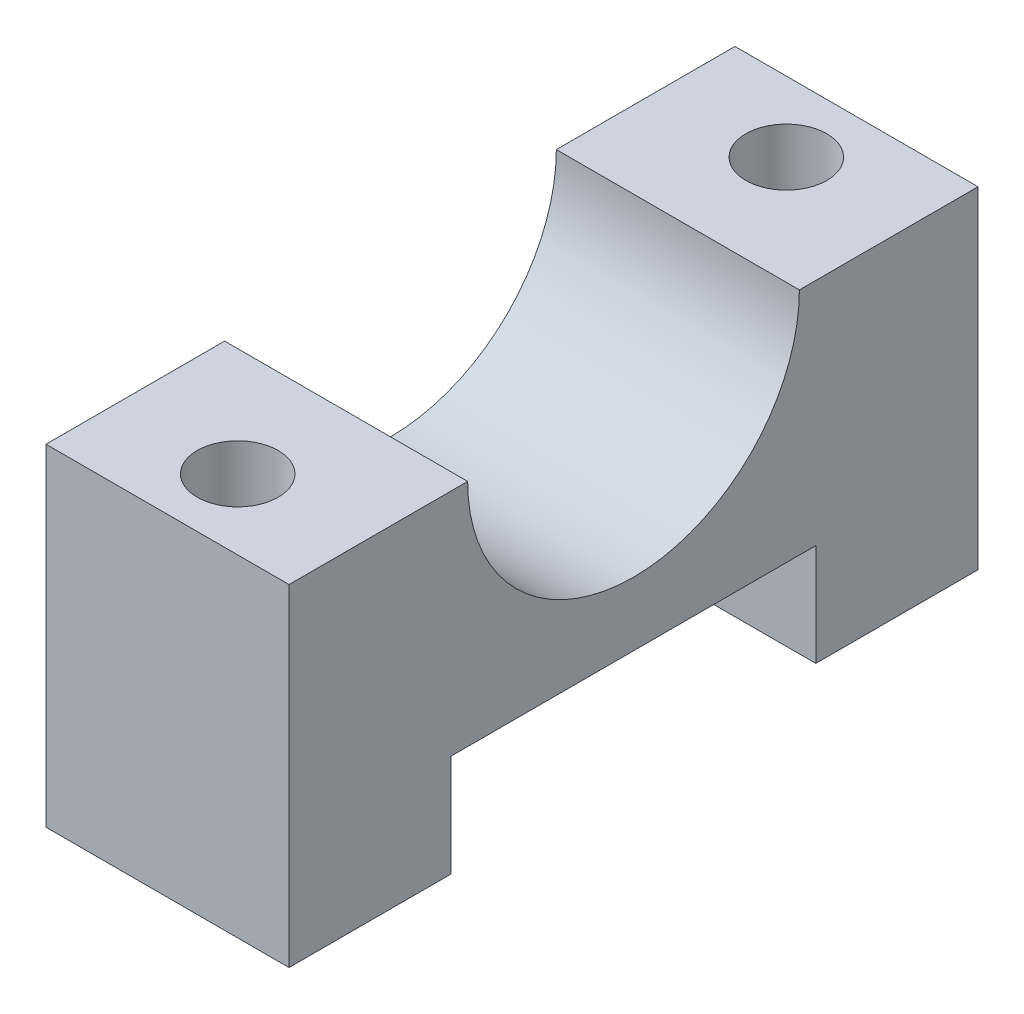
SolidWorks part; units mm, degrees
ref_plane "Front Plane" through (0, 0, 0) normal (0, 0, 1) x (1, 0, 0)
ref_plane "Top Plane" through (0, 0, 0) normal (0, 1, 0) x (1, 0, 0)
ref_plane "Right Plane" through (0, 0, 0) normal (1, 0, 0) x (0, 0, -1)
sketch "Sketch1" plane through (0, 0, 0) normal (1, 0, 0) x (0, 0, -1)
  line L0 (6.5, 0) -> (13.5, 0)
  line L1 (-13.5, 0) -> (-6.5, 0)
  line L2 (-13.5, 0) -> (-13.5, -13)
  line L3 (-13.5, -13) -> (13.5, -13)
  line L4 (13.5, 0) -> (13.5, -13)
  arc A0 (-6.5, 0) -> (6.5, 0) centre (0, 0) ccw
  dimension "D1" = 13
  dimension "D3" = 13
  dimension "D4" = 13.5
  dimension "D2" = 27
  dimension "D5" = 0
extrude "Boss-Extrude1" add sketch "Sketch1" along normal blind 9.525
sketch "Sketch3" plane through (9.525, 0, 0) normal (1, 0, 0) x (0, 0, -1)
  line L0 (-13.5, -13) -> (13.5, -13) construction
  line L1 (-7.1437, -9) -> (7.1438, -9)
  line L2 (-7.1437, -9) -> (-7.1437, -13)
  line L3 (-7.1437, -13) -> (7.1438, -13)
  line L4 (7.1438, -9) -> (7.1438, -13)
  dimension "D1" = 14.2875
  dimension "D2" = 7.1437
  dimension "D3" = 4
  dimension "D4" = 0
extrude "Cut-Extrude1" cut sketch "Sketch3" against normal through all
sketch "Sketch4" plane through (0, -13, 0) normal (0, -1, 0) x (1, 0, 0)
  line L3 (9.525, -13.5) -> (0, -13.5) construction
  line L5 (9.525, 13.5) -> (9.525, 7.1437) construction
  line L6 (9.525, -7.1438) -> (9.525, -13.5) construction
  line L7 (9.525, 13.5) -> (0, 13.5) construction
  circle A0 centre (4.7625, -10.75) radius 1.5875
  circle A1 centre (4.7625, 10.75) radius 1.5875
  dimension "D1" = 3.175
  dimension "D4" = 3.175
  dimension "D3" = 2.75
  dimension "D2" = 4.7625
  dimension "D5" = 4.7625
  dimension "D6" = 2.75
extrude "Cut-Extrude2" cut sketch "Sketch4" against normal through all
equation "\"D4@Sketch1\"=\"D2@Sketch1\"/2"
equation "\"D2@Sketch3\"=\"D1@Sketch3\"/2"
equation "\"D4@Sketch4\"=\"D1@Sketch4\""
equation "\"D2@Sketch4\"=\"D5@Sketch4\""
equation "\"D6@Sketch4\"=\"D3@Sketch4\""
